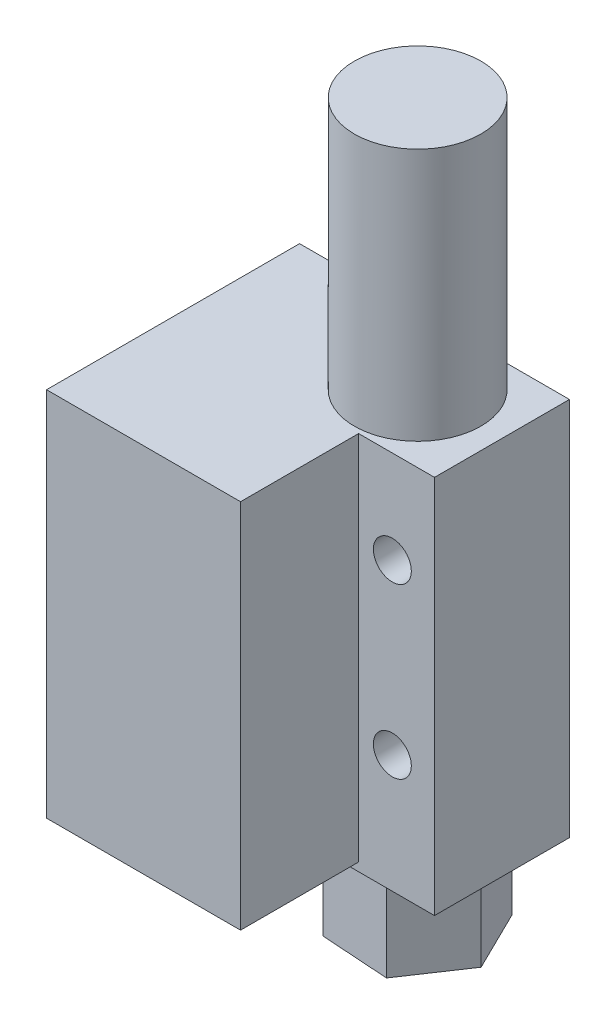
SolidWorks part; units mm, degrees
ref_plane "前视基准面" through (0, 0, 0) normal (0, 0, 1) x (1, 0, 0)
ref_plane "上视基准面" through (0, 0, 0) normal (0, 1, 0) x (1, 0, 0)
ref_plane "右视基准面" through (0, 0, 0) normal (1, 0, 0) x (0, 0, -1)
sketch "草图1" plane through (0, 0, 0) normal (0, 0, 1) x (1, 0, 0)
  line L1 (-16, 22.5) -> (16, 22.5)
  line L2 (-16, 22.5) -> (-16, -22.5)
  line L3 (-16, -22.5) -> (16, -22.5)
  line L4 (16, 22.5) -> (16, -22.5)
  line L5 (-16, 22.5) -> (16, -22.5) construction
  line L6 (-16, -22.5) -> (16, 22.5) construction
  point P1 (0, 0)
  dimension "D1" = 32
  dimension "D2" = 45
extrude "凸台-拉伸1" add sketch "草图1" along normal blind 16
sketch "草图2" plane through (0, 0, 0) normal (0, 0, -1) x (-1, 0, 0)
  line L0 (-16, 22.5) -> (16, 22.5) construction
  line L1 (-16, -22.5) -> (-16, 22.5) construction
  circle A0 centre (-11, 11.5) radius 2.25
  circle A1 centre (-11, -8.5) radius 2.25
  dimension "D1" = 11
  dimension "D2" = 20
  dimension "D3" = 5
extrude "切除-拉伸1" cut sketch "草图2" against normal up to next
sketch "草图3" plane through (0, 22.5, 0) normal (0, 1, 0) x (1, 0, 0)
  line L0 (16, -16) -> (-16, -16) construction
  line L2 (16, -16) -> (16, 0) construction
  circle A0 centre (6, -8) radius 7.5
  dimension "D1" = 15
  dimension "D2" = 8
  dimension "D3" = 10
extrude "凸台-拉伸2" add sketch "草图3" along normal blind 30
sketch "草图4" plane through (0, 0, 16) normal (0, 0, 1) x (1, 0, 0)
  line L1 (-16, 22.5) -> (-16, -21.5)
  line L3 (-16, 22.5) -> (7, 22.5)
  line L4 (-16, -21.5) -> (16, -21.5)
  line L5 (-16, -21.5) -> (7, -21.5)
  line L6 (7, 22.5) -> (7, -21.5)
  line L7 (-16, 22.5) -> (16, 22.5) construction
  line L8 (-16, -21.5) -> (16, -21.5) construction
  dimension "D1" = 1
  dimension "D2" = 44
extrude "凸台-拉伸3" add sketch "草图4" along normal blind 14
sketch "草图5" plane through (0, -22.5, 0) normal (0, -1, 0) x (1, 0, 0)
  line L0 (16, 16) -> (16, 0) construction
  line L1 (10.501, 1.2863) -> (14.0648, 8.5411)
  line L2 (14.0648, 8.5411) -> (9.5637, 15.2549)
  line L3 (9.5637, 15.2549) -> (1.499, 14.7137)
  line L4 (1.499, 14.7137) -> (-2.0648, 7.4589)
  line L5 (-2.0648, 7.4589) -> (2.4363, 0.7451)
  line L6 (2.4363, 0.7451) -> (10.501, 1.2863)
  line L7 (-16, 0) -> (16, 0) construction
  circle A0 centre (6, 8) radius 7 construction
  point P1 (16, 8)
  dimension "D1" = 14
  dimension "D2" = 10
  dimension "D3" = 8
extrude "凸台-拉伸4" add sketch "草图5" along normal blind 10
sketch "草图6" plane through (0, -32.5, 0) normal (0, -1, 0) x (1, 0, 0)
  line L0 (-2.0648, 7.4589) -> (14.0623, 8.536) construction
  line L1 (10.501, 1.2863) -> (14.0648, 8.5411) construction
  circle A0 centre (5.9959, 7.9973) radius 4.5271
extrude "切除-拉伸2" cut sketch "草图6" against normal blind 10
sketch "草图7" plane through (-16, 0, 0) normal (-1, 0, 0) x (0, 0, 1)
  line L0 (0, 22.5) -> (0, -22.5) construction
  line L1 (16, -22.5) -> (0, -22.5) construction
  circle A0 centre (8, -10.5) radius 4
  dimension "D3" = 8
  dimension "D1" = 8
  dimension "D2" = 12
extrude "切除-拉伸3" cut sketch "草图7" against normal blind 10
